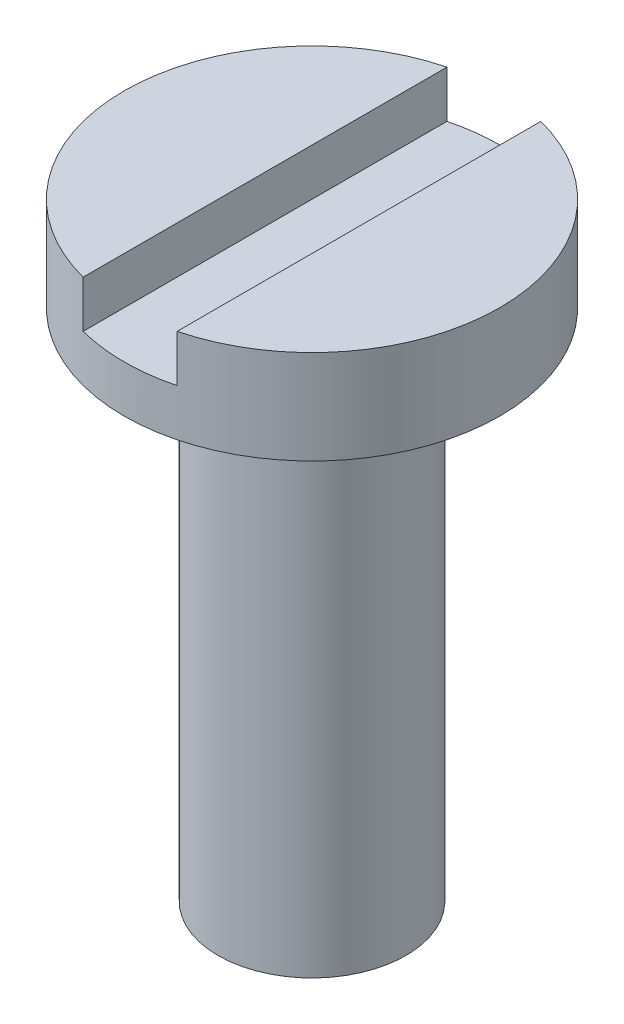
SolidWorks part; units mm, degrees
ref_plane "Plan de face" through (0, 0, 0) normal (0, 0, 1) x (1, 0, 0)
ref_plane "Plan de dessus" through (0, 0, 0) normal (0, 1, 0) x (1, 0, 0)
ref_plane "Plan de droite" through (0, 0, 0) normal (1, 0, 0) x (0, 0, -1)
sketch "Esquisse1" plane through (0, 0, 0) normal (0, 0, 1) x (1, 0, 0)
  line L0 (0, 0) -> (0, 9.7113)
  line L1 (0, 9.7113) -> (3, 9.7113)
  line L2 (3, 9.7113) -> (3, 8.2113)
  line L3 (3, 8.2113) -> (1.5, 8.2113)
  line L4 (1.5, 8.2113) -> (1.5, 0)
  line L5 (1.5, 0) -> (0, 0) construction
  line L6 (1.5, 8.2113) -> (0, 8.2113) construction
  line L7 (1.5, 0) -> (1, -0.2887)
  line L8 (1, -0.2887) -> (0, -0.2887)
  line L9 (0, -0.2887) -> (0, 0)
  line L10 (1, -0.2887) -> (1, 8.2113) construction
  dimension "D1" = 1.5
  dimension "D2" = 30
  dimension "D3" = 0.5
  dimension "D4" = 10
  dimension "D5" = 1.5
  dimension "D6" = 3
revolve "Révolution1" add sketch "Esquisse1" angle 360 about L0
sketch "Esquisse2" plane through (0, 0, 0) normal (0, 0, 1) x (1, 0, 0)
  line L0 (3, 9.7113) -> (-3, 9.7113) construction
  line L1 (-0.75, 9.7113) -> (0.75, 9.7113)
  line L2 (-0.75, 9.7113) -> (-0.75, 8.9613)
  line L3 (-0.75, 8.9613) -> (0.75, 8.9613)
  line L4 (0.75, 9.7113) -> (0.75, 8.9613)
  line L5 (-3, 9.7113) -> (-0.75, 9.7113) construction
  line L6 (0.75, 9.7113) -> (3, 9.7113) construction
  dimension "D1" = 0.75
  dimension "D2" = 1.5
extrude "Enlèv. mat.-Extru.1" cut sketch "Esquisse2" against normal through all both and the other way through all
